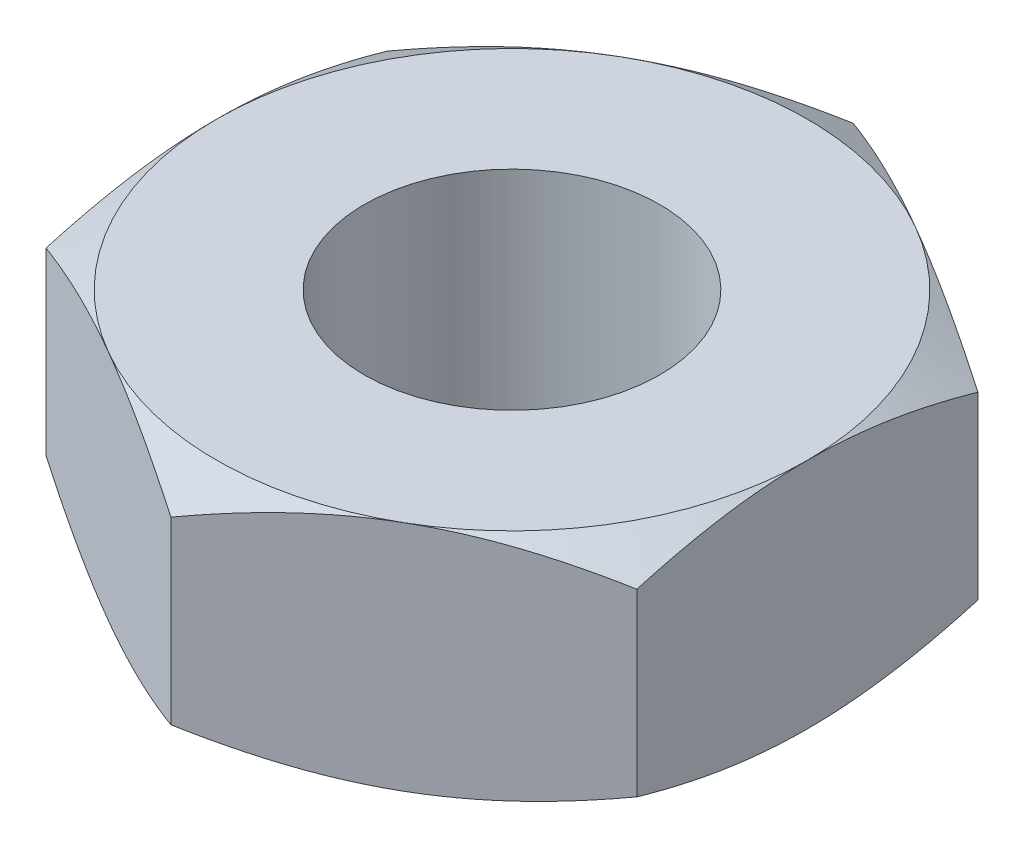
SolidWorks part; units mm, degrees
ref_plane "Front Plane" through (0, 0, 0) normal (0, 0, 1) x (1, 0, 0)
ref_plane "Top Plane" through (0, 0, 0) normal (0, 1, 0) x (1, 0, 0)
ref_plane "Right Plane" through (0, 0, 0) normal (1, 0, 0) x (0, 0, -1)
sketch "Sketch2" plane through (0, 0, 0) normal (0, 1, 0) x (1, 0, 0)
  line L1 (0, -14.6647) -> (12.7, -7.3323)
  line L2 (12.7, -7.3323) -> (12.7, 7.3323)
  line L3 (12.7, 7.3323) -> (0, 14.6647)
  line L4 (0, 14.6647) -> (-12.7, 7.3323)
  line L5 (-12.7, 7.3323) -> (-12.7, -7.3323)
  line L6 (-12.7, -7.3323) -> (0, -14.6647)
  circle A0 centre (0, 0) radius 12.7 construction
  circle A1 centre (0, 0) radius 6.35
  dimension "D2" = 12.7
  dimension "D1" = 25.4
extrude "Boss-Extrude1" add sketch "Sketch2" along normal mid plane 10
cosmetic thread "Cosmetic Thread1" parameters "D2"=16
sketch "Sketch3" plane through (0, 0, 0) normal (0, 0, 1) x (1, 0, 0)
  line L0 (0, 0) -> (0, -50000) construction
  line L2 (0, 0) -> (50000, 0) construction
  line L3 (12.7, 5) -> (15.7, 5)
  line L4 (12.7, -5) -> (15.7, -5)
  line L5 (15.7, 5) -> (15.7, 3.2679)
  line L6 (15.7, -5) -> (15.7, -3.2679)
  line L7 (15.7, 3.2679) -> (12.7, 5)
  line L8 (15.7, -3.2679) -> (12.7, -5)
  dimension "D1" = 30
  dimension "D2" = 3
revolve "Cut-Revolve1" cut sketch "Sketch3" angle 360 about L0
